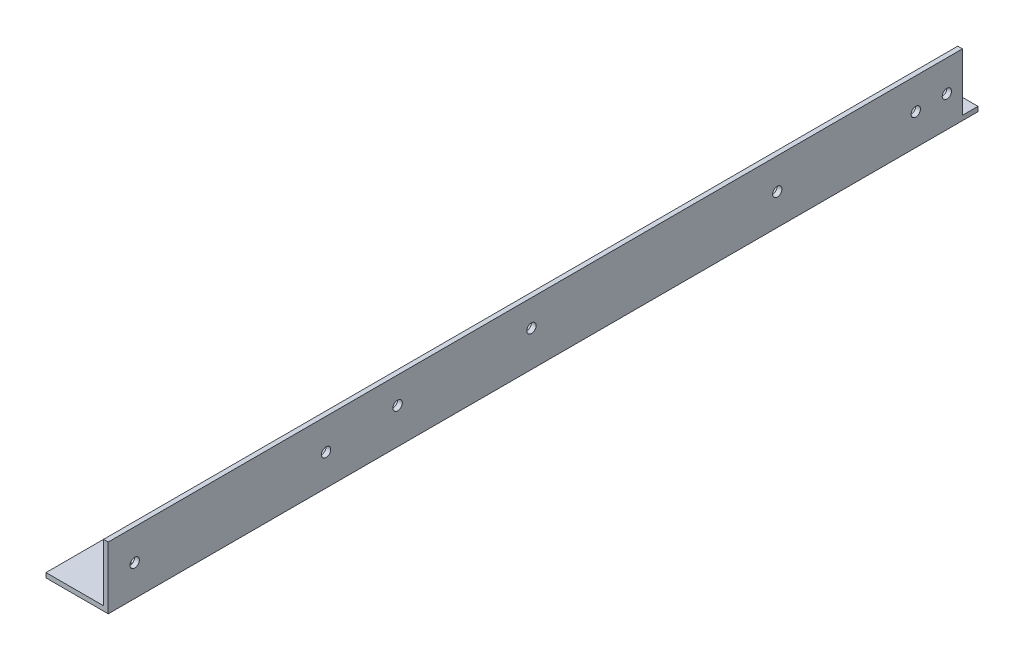
SolidWorks part; units mm, degrees
ref_plane "Plan de face" through (0, 0, 0) normal (0, 0, 1) x (1, 0, 0)
ref_plane "Plan de dessus" through (0, 0, 0) normal (0, 1, 0) x (1, 0, 0)
ref_plane "Plan de droite" through (0, 0, 0) normal (1, 0, 0) x (0, 0, -1)
sketch "Esquisse1" plane through (0, 0, 0) normal (0, 0, 1) x (1, 0, 0)
  line L0 (-17.4317, -13.7266) -> (-17.4317, -15.2266)
  line L1 (-17.4317, -15.2266) -> (2.5683, -15.2266)
  line L2 (2.5683, -15.2266) -> (2.5683, 4.7734)
  line L3 (1.0683, -13.7266) -> (-17.4317, -13.7266)
  line L4 (2.5683, 4.7734) -> (1.0683, 4.7734)
  line L5 (1.0683, 4.7734) -> (1.0683, -13.7266)
  dimension "D1" = 1.5
  dimension "D2" = 1.5
  dimension "D3" = 20
  dimension "D4" = 20
extrude "Extrusion1" add sketch "Esquisse1" along normal blind 274.5
sketch "Esquisse2" plane through (0, -13.7266, 0) normal (0, 1, 0) x (-1, 0, 0)
  line L0 (-1.0683, 274.5) -> (-1.0683, 0) construction
  line L1 (4.9317, 15.5) -> (4.9317, 4.5) construction
  line L2 (-1.0683, 0) -> (17.4317, 0) construction
  line L3 (-1.0683, 274.5) -> (17.4317, 274.5) construction
  line L4 (4.9317, 259.5) -> (4.9317, 248.5) construction
  line L5 (17.4317, 274.5) -> (17.4317, 0) construction
  circle A1 centre (7.4317, 204.5) radius 1.5
  circle A2 centre (4.9317, 4.5) radius 2
  circle A3 centre (4.9317, 15.5) radius 2
  circle A4 centre (4.9317, 248.5) radius 2
  circle A5 centre (4.9317, 259.5) radius 2
  circle A6 centre (7.4317, 59.5) radius 1.5
  point P2 (8.1817, 274.5)
  dimension "D1" = 15
  dimension "D5" = 11
  dimension "D7" = 11
  dimension "D9" = 70
  dimension "D4" = 6
  dimension "D6" = 4.5
  dimension "D8" = 6
  dimension "D10" = 59.5
  dimension "D11" = 10
  dimension "D12" = 10
extrude "Extrusion2" cut sketch "Esquisse2" against normal blind 300
sketch "Esquisse3" plane through (2.5683, 0, 0) normal (1, 0, 0) x (0, 0, -1)
  line L0 (-274.5, 4.7734) -> (0, 4.7734) construction
  line L1 (-274.5, -15.2266) -> (-274.5, 4.7734) construction
  line L2 (0, -15.2266) -> (0, 4.7734) construction
  line L3 (-274.5, -15.2266) -> (0, -15.2266) construction
  circle A0 centre (-266, -5.2266) radius 1.5
  circle A1 centre (-5, -5.2266) radius 1.5
  circle A2 centre (-15, -5.2266) radius 1.5
  circle A3 centre (-59.5, -5.2266) radius 1.5
  circle A4 centre (-204.5, -5.2266) radius 1.5
  circle A5 centre (-181.5, -3.7266) radius 1.5
  circle A6 centre (-138.5, -3.7266) radius 1.5
  point P10 (0, -5.2266)
  dimension "D1" = 10
  dimension "D3" = 10
  dimension "D5" = 10
  dimension "D7" = 70
  dimension "D9" = 23
  dimension "D2" = 8.5
  dimension "D4" = 5
  dimension "D6" = 59.5
  dimension "D8" = 10
  dimension "D10" = 43
  dimension "D11" = 8.5
  dimension "D12" = 8.5
extrude "Extrusion3" cut sketch "Esquisse3" against normal blind 10
sketch "Esquisse4" plane through (0, 0, 0) normal (0, 0, -1) x (-1, 0, 0)
  line L0 (-2.5683, -15.2266) -> (-2.5683, 4.7734) construction
  line L1 (17.4317, -15.2266) -> (-2.5683, -15.2266)
  line L2 (17.4317, -15.2266) -> (17.4317, -13.7266)
  line L3 (17.4317, -13.7266) -> (-2.5683, -13.7266)
  line L4 (-2.5683, -15.2266) -> (-2.5683, -13.7266)
  dimension "D1" = 1.5
extrude "Extrusion4" add sketch "Esquisse4" along normal blind 5
